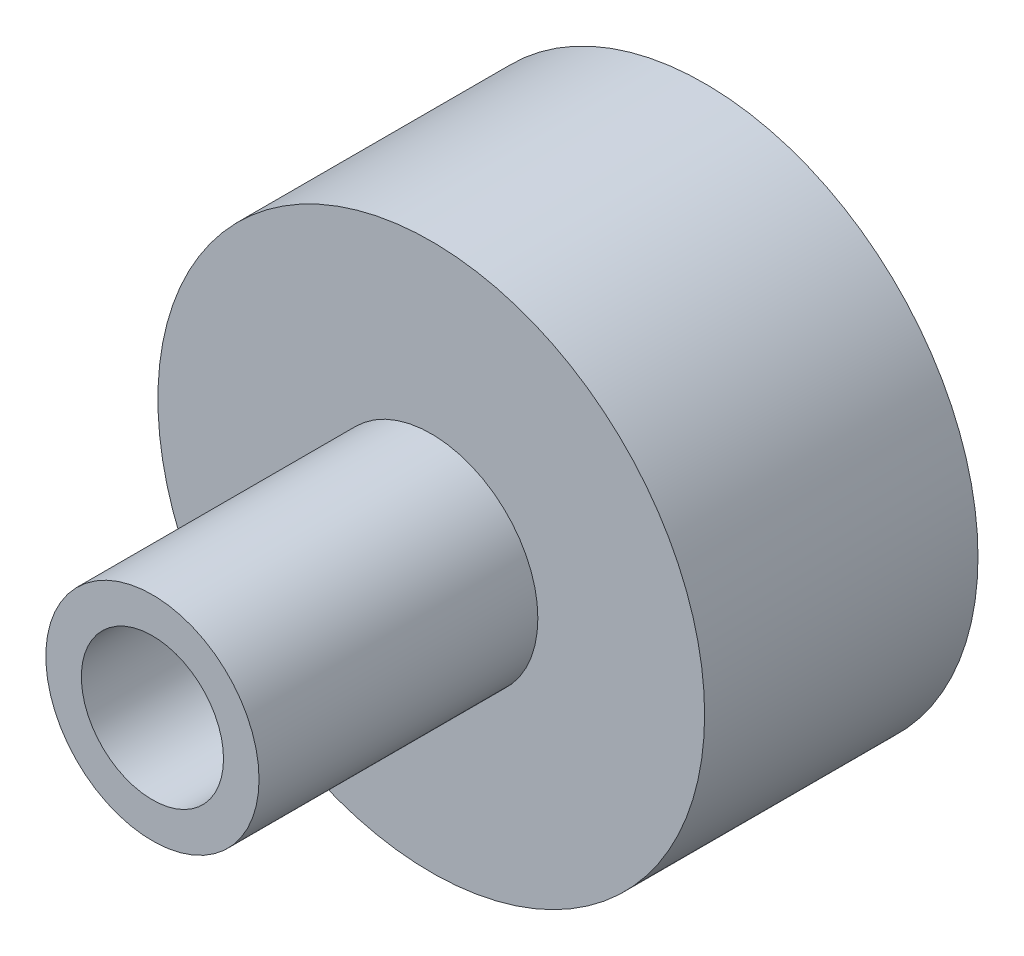
SolidWorks part; units mm, degrees
ref_plane "정면" through (0, 0, 0) normal (0, 0, 1) x (1, 0, 0)
ref_plane "윗면" through (0, 0, 0) normal (0, 1, 0) x (1, 0, 0)
ref_plane "우측면" through (0, 0, 0) normal (1, 0, 0) x (0, 0, -1)
sketch "Sketch1" plane through (0, 0, 0) normal (0, 0, 1) x (1, 0, 0)
  circle A0 centre (0, 0) radius 10
  dimension "D1" = 20
extrude "Extrude1" add sketch "Sketch1" along normal blind 10
sketch "Sketch2" plane through (0, 0, 10) normal (0, 0, 1) x (1, 0, 0)
  circle A0 centre (0, 0) radius 3.9
  dimension "D1" = 7.8
extrude "Extrude2" add sketch "Sketch2" along normal blind 10.2
sketch "Sketch3" plane through (0, 0, 20.2) normal (0, 0, 1) x (1, 0, 0)
  circle A0 centre (0, 0) radius 2.6
  dimension "D1" = 5.2
extrude "Extrude3" cut sketch "Sketch3" against normal up to next
